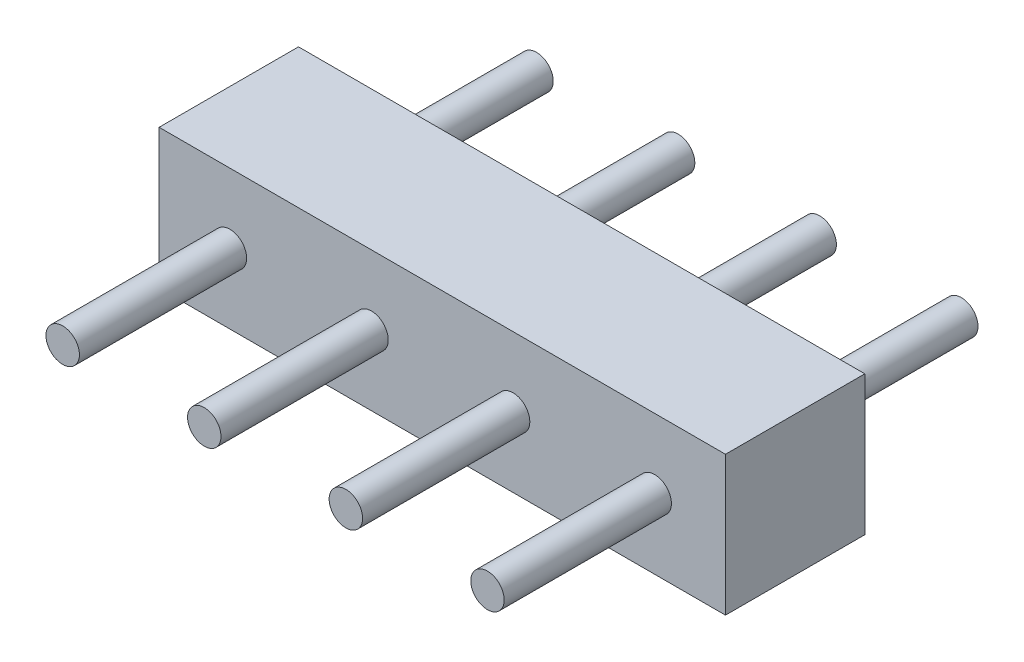
SolidWorks part; units mm, degrees
ref_plane "前视基准面" through (0, 0, 0) normal (0, 0, 1) x (1, 0, 0)
ref_plane "上视基准面" through (0, 0, 0) normal (0, 1, 0) x (1, 0, 0)
ref_plane "右视基准面" through (0, 0, 0) normal (1, 0, 0) x (0, 0, -1)
sketch "草图1" plane through (0, 0, 0) normal (0, 0, 1) x (1, 0, 0)
  line L1 (0, 0) -> (10.16, 0)
  line L2 (0, 0) -> (0, 2.5)
  line L3 (0, 2.5) -> (10.16, 2.5)
  line L4 (10.16, 0) -> (10.16, 2.5)
  dimension "D1" = 2.5
  dimension "D2" = 10.16
extrude "凸台-拉伸1" add sketch "草图1" along normal blind 2.5
sketch "草图2" plane through (0, 0, 2.5) normal (0, 0, 1) x (1, 0, 0)
  line L0 (5.08, 2.5) -> (5.08, -1.7995) construction
  line L1 (10.16, 2.5) -> (0, 2.5) construction
  line L2 (0, 1.25) -> (15.9024, 1.25) construction
  line L3 (0, 2.5) -> (0, 0) construction
  circle A0 centre (3.81, 1.25) radius 0.3
  dimension "D1" = 1.27
  dimension "D2" = 0.6
extrude "凸台-拉伸2" add sketch "草图2" along normal blind 3 and the other way blind 5.5
pattern_linear "阵列(线性)1" count 3 spacing 2.54 along (1, 0, 0) count 2 spacing 2.54 along (-1, 0, 0) of "凸台-拉伸2"
